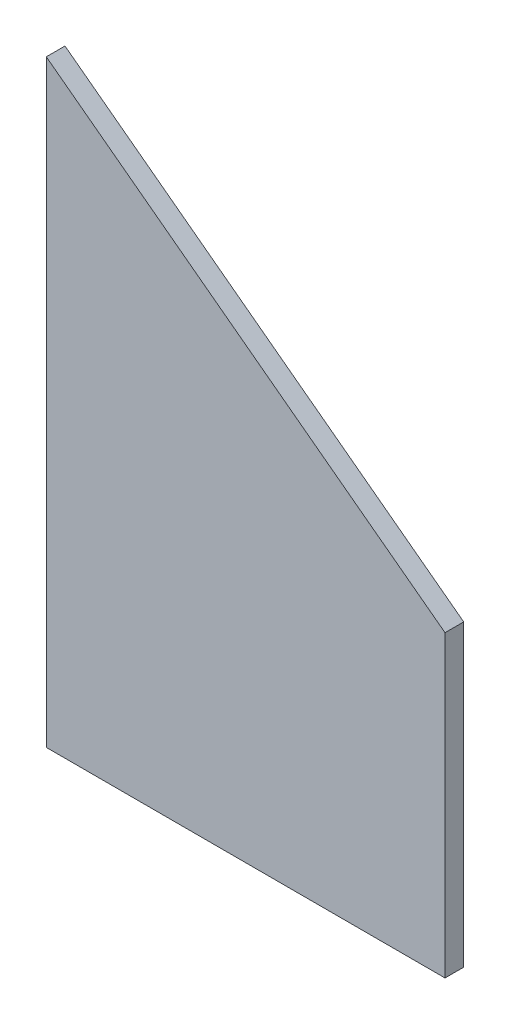
SolidWorks part; units mm, degrees
ref_plane "Front Plane" through (0, 0, 0) normal (0, 0, 1) x (1, 0, 0)
ref_plane "Top Plane" through (0, 0, 0) normal (0, 1, 0) x (1, 0, 0)
ref_plane "Right Plane" through (0, 0, 0) normal (1, 0, 0) x (0, 0, -1)
sketch "Sketch1" plane through (0, 0, 0) normal (0, 0, 1) x (1, 0, 0)
  line L0 (0, -76.2) -> (0, 76.2)
  line L1 (0, 76.2) -> (101.6, -0.0834)
  line L2 (101.6, -0.0834) -> (0, 76.2)
  line L3 (0, 76.2) -> (37.2108, 76.2) construction
  line L4 (101.6, -0.0834) -> (101.6, -76.2834)
  line L5 (101.6, -76.2834) -> (0, -76.2)
  point P4 (0, 0)
  dimension "D1" = 152.4
  dimension "D2" = 36.9
  dimension "D3" = 76.2
  dimension "D4" = 101.6
extrude "Boss-Extrude1" add sketch "Sketch1" along normal blind 4.7625 contours L5 L4 L1 L0
